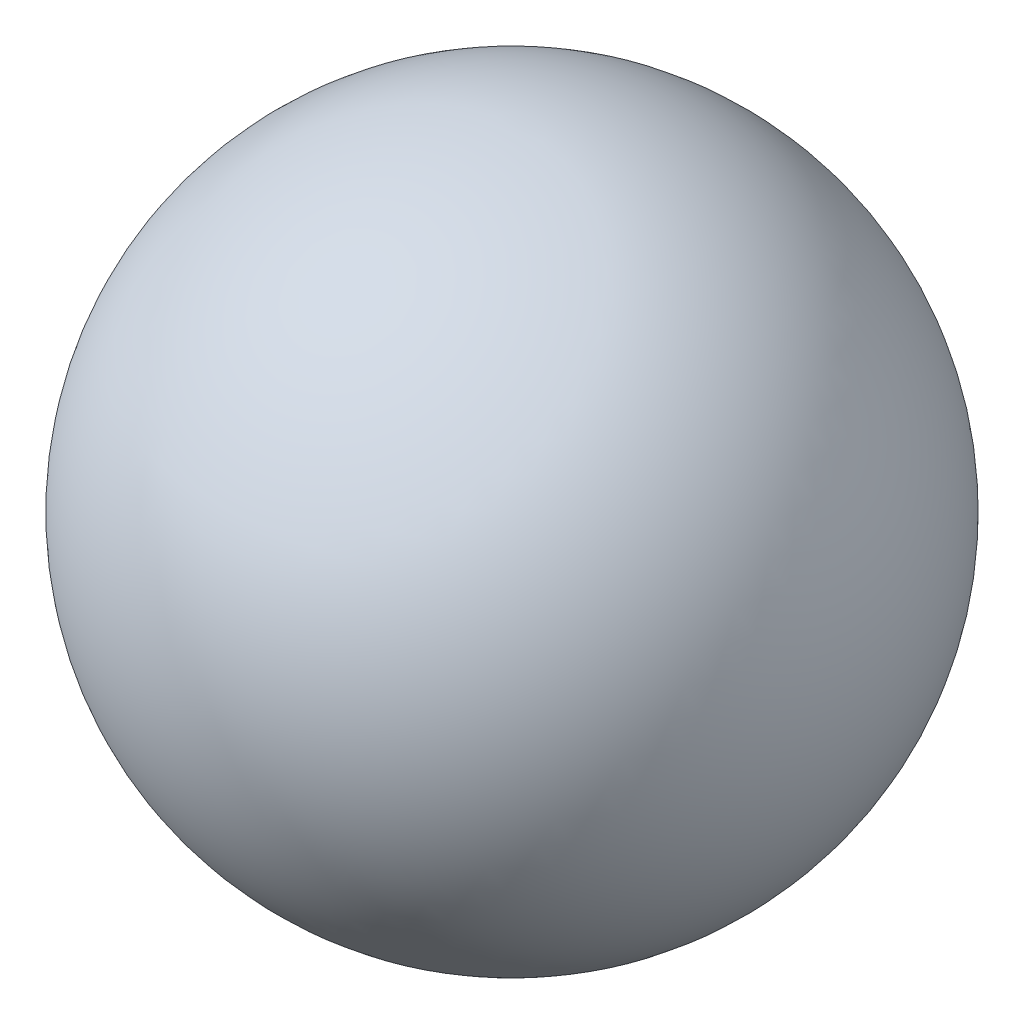
SolidWorks part; units mm, degrees
material "BUTYL"
ref_plane "Front Plane" through (0, 0, 0) normal (0, 0, 1) x (1, 0, 0)
ref_plane "Top Plane" through (0, 0, 0) normal (0, 1, 0) x (1, 0, 0)
ref_plane "Right Plane" through (0, 0, 0) normal (1, 0, 0) x (0, 0, -1)
sketch "Sketch1" plane through (0, 0, 0) normal (0, 0, 1) x (1, 0, 0)
  line L0 (0, 0) -> (0, 600)
  arc A0 (0, 600) -> (0, 0) centre (0, 300) cw
  dimension "D2" = 300
  dimension "D1" = 600
revolve "Revolve1" add sketch "Sketch1" angle 360 about L0
